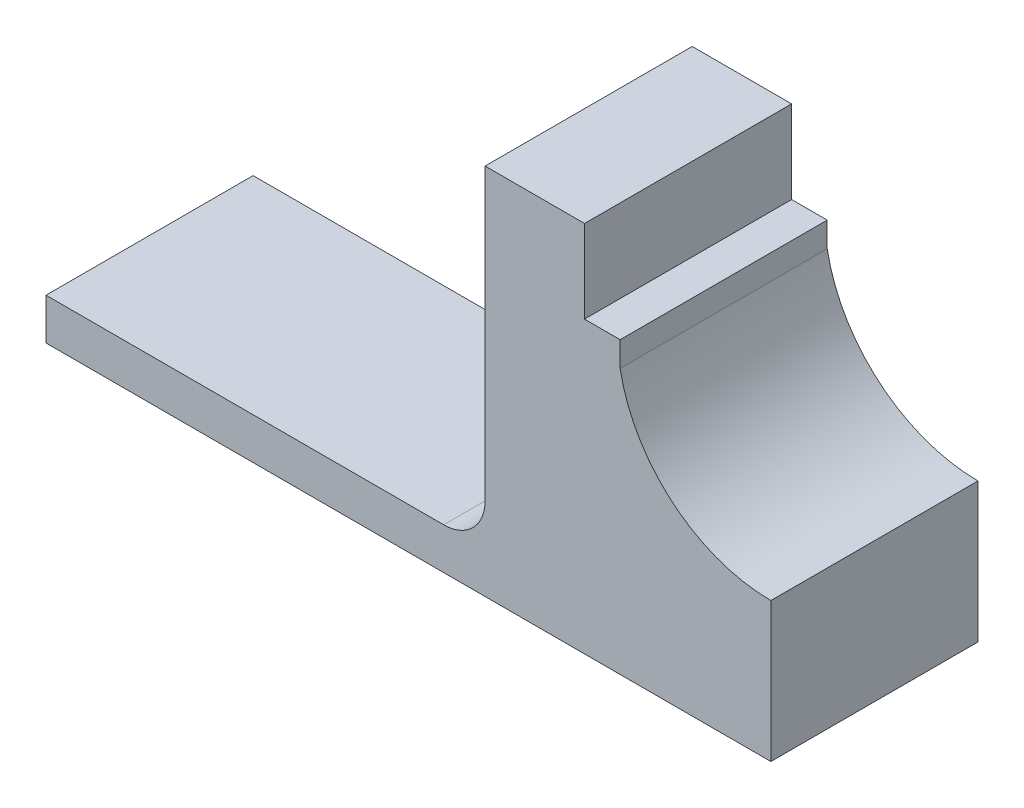
SolidWorks part; units mm, degrees
ref_plane "Front Plane" through (0, 0, 0) normal (0, 0, 1) x (1, 0, 0)
ref_plane "Top Plane" through (0, 0, 0) normal (0, 1, 0) x (1, 0, 0)
ref_plane "Right Plane" through (0, 0, 0) normal (1, 0, 0) x (0, 0, -1)
sketch "Sketch3" plane through (0, 0, 0) normal (0, 0, 1) x (1, 0, 0)
  line L0 (-2079.2127, -769.8632) -> (-860.0127, -769.8632)
  line L1 (-733.0127, 246.1368) -> (-428.1506, 246.1368)
  line L2 (-2079.2127, -769.8632) -> (-2079.2127, -896.8632)
  line L3 (-2079.2127, -896.8632) -> (143.2873, -896.8632)
  line L4 (143.2873, -469.3379) -> (143.2873, -896.8632)
  line L5 (-733.0127, -642.8632) -> (-733.0127, 246.1368)
  line L6 (-428.1506, 246.1368) -> (-428.1506, -7.8632)
  line L7 (-428.1506, -7.8632) -> (-326.6127, -7.8632)
  line L8 (-318.9297, -84.0632) -> (-318.9297, -7.8632)
  line L9 (-318.9297, -7.8632) -> (-326.6127, -7.8632)
  arc A0 (-860.0127, -769.8632) -> (-733.0127, -642.8632) centre (-860.0127, -642.8632) ccw
  arc A1 (-318.9297, -84.0632) -> (143.2873, -469.3379) centre (143.2873, 0.5621) ccw
  point P9 (-733.0127, -769.8632)
  dimension "D5" = 127
  dimension "D7" = 939.8
  dimension "D1" = 2222.5
  dimension "D2" = 1143
  dimension "D3" = 1346.2
  dimension "D4" = 127
  dimension "D6" = 571.5
  dimension "D8" = 254
  dimension "D9" = 76.2
extrude "Boss-Extrude1" add sketch "Sketch3" along normal blind 635
